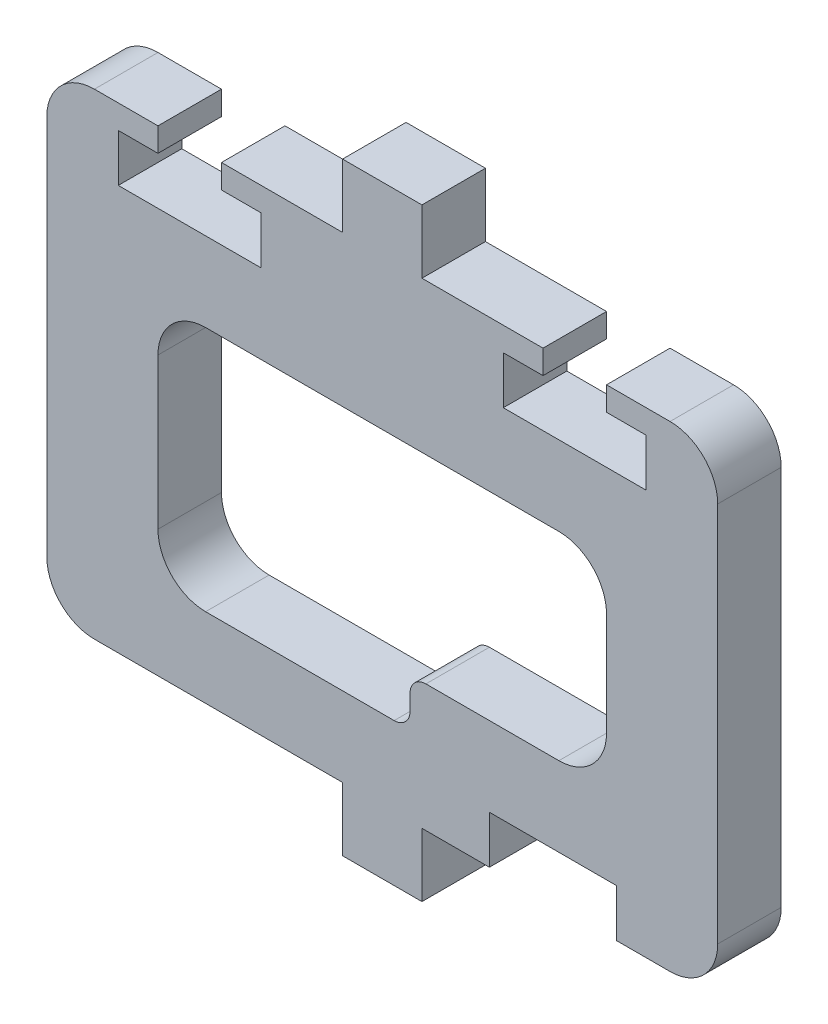
SolidWorks part; units mm, degrees
ref_plane "Alzado" through (0, 0, 0) normal (0, 0, 1) x (1, 0, 0)
ref_plane "Planta" through (0, 0, 0) normal (0, 1, 0) x (1, 0, 0)
ref_plane "Vista lateral" through (0, 0, 0) normal (1, 0, 0) x (0, 0, -1)
sketch "Croquis1" plane through (0, 0, 0) normal (0, 0, 1) x (1, 0, 0)
  line L0 (-102.6151, -94.222) -> (-98.3651, -94.222)
  line L1 (-98.3651, -94.222) -> (-98.3651, -91.222)
  line L2 (-107.6151, -60.222) -> (-105.1151, -60.222)
  line L3 (-102.6151, -64.222) -> (-94.9901, -64.222)
  line L4 (-107.6151, -94.222) -> (-123.2401, -94.222)
  line L5 (-105.1151, -60.222) -> (-102.6151, -60.222)
  line L6 (-102.6151, -60.222) -> (-102.6151, -64.222)
  line L7 (-94.9901, -64.222) -> (-94.9901, -65.722)
  line L8 (-94.9901, -65.722) -> (-97.4901, -65.722)
  line L9 (-97.4901, -65.722) -> (-97.4901, -68.722)
  line L10 (-97.4901, -68.722) -> (-88.4901, -68.722)
  line L11 (-88.4901, -68.722) -> (-88.4901, -65.722)
  line L12 (-88.4901, -65.722) -> (-90.9901, -65.722)
  line L13 (-90.9901, -65.722) -> (-90.9901, -64.222)
  line L14 (-119.2401, -64.222) -> (-123.2401, -64.222)
  line L15 (-83.9901, -91.222) -> (-83.9901, -67.222)
  line L16 (-90.9901, -64.222) -> (-86.9901, -64.222)
  line L17 (-119.2401, -65.722) -> (-119.2401, -64.222)
  line L18 (-121.7401, -65.722) -> (-119.2401, -65.722)
  line L19 (-121.7401, -68.722) -> (-121.7401, -65.722)
  line L20 (-121.7401, -68.722) -> (-112.7401, -68.722)
  line L21 (-112.7401, -65.722) -> (-112.7401, -68.722)
  line L22 (-115.2401, -65.722) -> (-112.7401, -65.722)
  line L23 (-115.2401, -64.222) -> (-115.2401, -65.722)
  line L24 (-107.6151, -60.222) -> (-107.6151, -64.222)
  line L25 (-107.6151, -64.222) -> (-115.2401, -64.222)
  line L26 (-107.6151, -98.222) -> (-107.6151, -94.222)
  line L27 (-102.6151, -98.222) -> (-102.6151, -94.222)
  line L28 (-105.1151, -98.222) -> (-102.6151, -98.222)
  line L29 (-107.6151, -98.222) -> (-105.1151, -98.222)
  line L30 (-98.3651, -91.222) -> (-90.3651, -91.222)
  line L31 (-90.3651, -91.222) -> (-90.3651, -94.222)
  line L32 (-126.2401, -91.222) -> (-126.2401, -67.222)
  line L33 (-86.9901, -94.222) -> (-90.3651, -94.222)
  arc A0 (-126.2401, -91.222) -> (-123.2401, -94.222) centre (-123.2401, -91.222) ccw
  arc A1 (-86.9901, -94.222) -> (-83.9901, -91.222) centre (-86.9901, -91.222) ccw
  arc A2 (-83.9901, -67.222) -> (-86.9901, -64.222) centre (-86.9901, -67.222) ccw
  arc A3 (-126.2401, -67.222) -> (-123.2401, -64.222) centre (-123.2401, -67.222) cw
  dimension "D1" = 3
extrude "Saliente-Extruir1" add sketch "Croquis1" along normal blind 4
sketch "Croquis2" plane through (0, 0, 4) normal (0, 0, 1) x (1, 0, 0)
  line L2 (-102.3651, -86.222) -> (-93.9901, -86.222)
  line L4 (-90.9901, -83.222) -> (-90.9901, -76.722)
  line L5 (-116.2401, -89.222) -> (-104.3651, -89.222)
  line L6 (-103.3651, -88.222) -> (-103.3651, -87.222)
  line L7 (-116.2401, -73.722) -> (-93.9901, -73.722)
  line L9 (-119.2401, -76.722) -> (-119.2401, -86.222)
  arc A0 (-119.2401, -86.222) -> (-116.2401, -89.222) centre (-116.2401, -86.222) ccw
  arc A1 (-93.9901, -86.222) -> (-90.9901, -83.222) centre (-93.9901, -83.222) ccw
  arc A2 (-90.9901, -76.722) -> (-93.9901, -73.722) centre (-93.9901, -76.722) ccw
  arc A3 (-116.2401, -73.722) -> (-119.2401, -76.722) centre (-116.2401, -76.722) ccw
  arc A4 (-104.3651, -89.222) -> (-103.3651, -88.222) centre (-104.3651, -88.222) ccw
  arc A5 (-103.3651, -87.222) -> (-102.3651, -86.222) centre (-102.3651, -87.222) cw
  dimension "D1" = 3
  dimension "D2" = 3
  dimension "D3" = 1
extrude "Cortar-Extruir1" cut sketch "Croquis2" against normal blind 4
